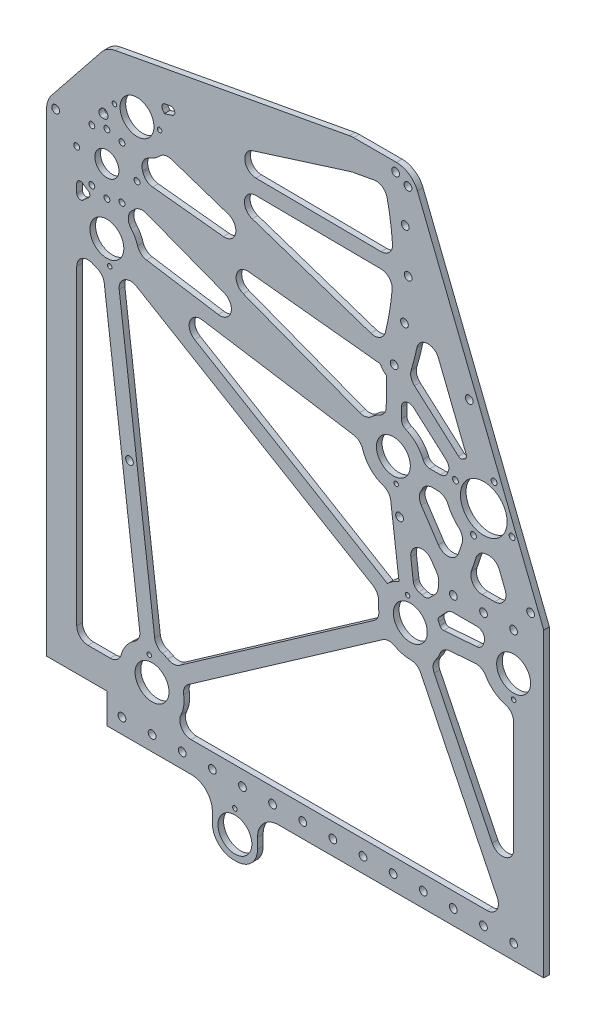
SolidWorks part; units mm, degrees
material "6061 Alloy"
ref_plane "Front Plane" through (0, 0, 0) normal (0, 0, 1) x (1, 0, 0)
ref_plane "Top Plane" through (0, 0, 0) normal (0, 1, 0) x (1, 0, 0)
ref_plane "Right Plane" through (0, 0, 0) normal (1, 0, 0) x (0, 0, -1)
sketch "Sketch1" plane through (0, 0, 0) normal (0, 0, 1) x (1, 0, 0)
  line L0 (0, 0) -> (0, 25.4) construction
  line L1 (0, 25.4) -> (-50.8, 25.4) construction
  line L2 (0, 0) -> (58.42, 0)
  line L3 (-50.8, 25.4) -> (-50.8, 457.2) construction
  line L4 (-50.8, 457.2) -> (12.7, 457.2) construction
  line L6 (76.2, -17.78) -> (76.2, -26.67)
  line L7 (93.98, -44.45) -> (96.52, -44.45)
  line L8 (114.3, -26.67) -> (114.3, -17.78)
  line L9 (132.08, 0) -> (355.6, 0)
  line L11 (355.6, 254) -> (355.6, 0)
  line L12 (249.1012, 521.3987) -> (355.6, 254)
  line L13 (330.2, 241.3) -> (304.8, 241.3) construction
  line L14 (305.0409, 317.5) -> (313.7282, 341.3682) construction
  line L15 (305.0409, 317.5) -> (313.7282, 341.3682) construction
  line L16 (-12.7, 355.6) -> (25.4, 50.8) construction
  line L17 (228.8409, 317.5) -> (243.1284, 203.2) construction
  line L19 (235.9847, 260.35) -> (2.849, 231.208) construction
  line L24 (-12.7, 435.6959) -> (12.7, 410.2959) construction
  line L25 (-12.7, 410.2959) -> (293.3509, 410.2959) construction
  line L27 (-63.5, 25.4) -> (-63.5, 425.1176)
  line L29 (0, 0) -> (-12.7, 0)
  line L30 (-12.7, 0) -> (-12.7, 25.4)
  line L31 (-63.5, 25.4) -> (-12.7, 25.4)
  line L32 (241.1463, 520.7) -> (292.8368, 390.9149) construction
  line L33 (12.7, 457.2) -> (229.4868, 384.6642) construction
  line L34 (12.7, 457.2) -> (229.4868, 384.6642) construction
  line L35 (12.7, 457.2) -> (238.1649, 419.4701) construction
  line L36 (12.7, 457.2) -> (230.7197, 525.9413) construction
  line L37 (195.2663, 533.4) -> (231.4032, 533.4)
  line L39 (191.8054, 533.083) -> (-5.7197, 496.5896)
  line L40 (-17.1343, 489.7571) -> (-59.3256, 437.0181)
  circle A0 centre (12.7, 457.2) radius 14.2875
  circle A1 centre (0, 12.7) radius 3.2639
  circle A3 centre (95.25, -25.4) radius 14.2875
  circle A4 centre (95.25, -6.35) radius 1.8987
  circle A5 centre (330.2, 209.55) radius 14.2875
  circle A6 centre (330.2, 241.3) radius 3.2639
  circle A7 centre (304.8, 241.3) radius 3.2639
  circle A8 centre (279.4, 241.3) radius 3.2639
  circle A9 centre (330.2, 190.5) radius 1.8987
  circle A10 centre (-6.35, 457.2) radius 1.8986
  circle A11 centre (31.75, 457.2) radius 1.8986
  circle A12 centre (-12.7, 410.2959) radius 25.4 construction
  circle A13 centre (-12.7, 435.6959) radius 2.4892
  circle A14 centre (12.7, 410.2959) radius 2.4892
  circle A15 centre (-12.7, 384.8959) radius 2.4892
  circle A17 centre (-12.7, 410.2959) radius 10.16
  circle A18 centre (305.0409, 317.5) radius 19.685
  circle A27 centre (-12.7, 355.6) radius 14.2875
  circle A28 centre (25.4, 50.8) radius 14.2875
  circle A29 centre (228.8409, 317.5) radius 14.2875
  circle A30 centre (243.1284, 203.2) radius 14.2875
  circle A31 centre (305.0409, 317.5) radius 25.4 construction
  circle A33 centre (313.7282, 341.3682) radius 2.4892
  circle A36 centre (328.9091, 308.8127) radius 2.4892
  circle A37 centre (296.3536, 293.6318) radius 2.4892
  circle A38 centre (281.1727, 326.1873) radius 2.4892
  circle A39 centre (241.1463, 520.7) radius 3.2639
  circle A41 centre (6.35, 203.2) radius 3.2639
  circle A43 centre (234.0392, 275.9136) radius 3.2639
  circle A48 centre (25.4, 12.7) radius 3.2639
  circle A50 centre (50.8, 12.7) radius 3.2639
  circle A51 centre (0, 388.2988) radius 2.4892
  circle A52 centre (-25.4, 388.2988) radius 2.4892
  circle A53 centre (-10.3371, 336.6971) radius 1.8986
  circle A54 centre (23.0371, 69.7029) radius 1.8986
  circle A55 centre (231.2038, 298.5971) radius 1.8986
  circle A56 centre (240.7656, 222.1029) radius 1.8987
  circle A57 centre (292.8368, 390.9149) radius 3.2639
  circle A58 centre (344.5273, 261.1297) radius 3.2639
  circle A59 centre (229.4868, 384.6642) radius 3.2639
  circle A60 centre (238.1649, 419.4701) radius 3.2639
  circle A61 centre (241.2913, 455.2051) radius 3.2639
  circle A62 centre (238.789, 490.9892) radius 3.2639
  circle A63 centre (230.7197, 525.9413) radius 3.2639
  arc A64 (114.3, -26.67) -> (96.52, -44.45) centre (96.52, -26.67) cw
  arc A65 (76.2, -26.67) -> (93.98, -44.45) centre (93.98, -26.67) ccw
  arc A66 (58.42, 0) -> (76.2, -17.78) centre (58.42, -17.78) cw
  arc A67 (132.08, 0) -> (114.3, -17.78) centre (132.08, -17.78) ccw
  arc A68 (249.1012, 521.3987) -> (231.4032, 533.4) centre (231.4032, 514.35) ccw
  arc A69 (195.2663, 533.4) -> (191.8054, 533.083) centre (195.2663, 514.35) ccw
  arc A70 (-63.5, 425.1176) -> (-59.3256, 437.0181) centre (-44.45, 425.1176) cw
  arc A71 (-5.7197, 496.5896) -> (-17.1343, 489.7571) centre (-2.2588, 477.8567) ccw
  circle A72 centre (-55.88, 428.625) radius 3.2639
  circle A82 centre (76.2, 12.7) radius 3.2639
  circle A83 centre (101.6, 12.7) radius 3.2639
  circle A84 centre (127, 12.7) radius 3.2639
  circle A85 centre (152.4, 12.7) radius 3.2639
  circle A86 centre (177.8, 12.7) radius 3.2639
  circle A87 centre (203.2, 12.7) radius 3.2639
  circle A88 centre (228.6, 12.7) radius 3.2639
  circle A89 centre (254, 12.7) radius 3.2639
  circle A90 centre (279.4, 12.7) radius 3.2639
  circle A91 centre (304.8, 12.7) radius 3.2639
  circle A92 centre (330.2, 12.7) radius 3.2639
  circle A93 centre (-38.1, 410.2959) radius 2.4892
  circle A94 centre (-25.4, 432.2929) radius 2.4892
  circle A95 centre (0, 432.2929) radius 2.4892
  circle A96 centre (-38.1, 410.2959) radius 2.4892 [skipped]
  point P51 (-12.7, 410.2959)
  point P126 (114.3, -44.45)
  point P129 (76.2, -44.45)
  point P132 (76.2, 0)
  point P135 (114.3, 0)
  point P139 (244.3213, 533.4)
  point P142 (193.5213, 533.4)
  point P145 (-63.5, 431.8)
  point P148 (-12.7, 495.3)
  point P173 (-12.7, 410.2959)
  dimension "D8" = 19.05
  dimension "D11" = 6.5278
  dimension "D14" = 19.05
  dimension "D15" = 6
  dimension "D22" = 3.7973
  dimension "D25" = 12.7
  dimension "D29" = 3
  dimension "D31" = 12.7
  dimension "D35" = 63.5
  dimension "D36" = 50.8
  dimension "D37" = 4.9784
  dimension "D41" = 20.32
  dimension "D44" = 28.575
  dimension "D43" = 39.37
  dimension "D52" = 50.8
  dimension "D53" = 139.7
  dimension "D69" = 14
  dimension "D13" = 19.05
  dimension "D55" = 533.4
  dimension "D66" = 17.78
  dimension "D75" = 19.05
  dimension "D76" = 7.62
  dimension "D1" = 50.8
  dimension "D2" = 355.6
  dimension "D3" = 25.4
  dimension "D4" = 63.5
  dimension "D5" = 431.8
  dimension "D6" = 431.8
  dimension "D7" = 304.8
  dimension "D9" = 12.7
  dimension "D10" = 53.34
  dimension "D12" = 19.05
  dimension "D16" = 25.4
  dimension "D17" = 19.05
  dimension "D18" = 44.45
  dimension "D19" = 127
  dimension "D20" = 38.1
  dimension "D21" = 19.05
  dimension "D23" = 209.55
  dimension "D24" = 25.4
  dimension "D26" = 254
  dimension "D27" = 76.2
  dimension "D28" = 31.75
  dimension "D30" = 25.4
  dimension "D32" = 19.05
  dimension "D33" = 19.05
  dimension "D34" = 19.05
  dimension "D38" = 25.4
  dimension "D39" = 3
  dimension "D42" = 203.2
  dimension "D45" = 50.8
  dimension "D46" = 76.2
  dimension "D47" = 355.6
  dimension "D48" = 38.1
  dimension "D49" = 139.7
  dimension "D50" = 25.4
  dimension "D51" = 234.95
  dimension "D54" = 228.6
  dimension "D57" = 70
  dimension "D58" = 25.4
  dimension "D59" = 12.7
  dimension "D60" = 3.175
  dimension "D63" = 5
  dimension "D64" = 9
  dimension "D68" = 17.5
  dimension "D70" = 406.4
  dimension "D71" = 50.8
  dimension "D72" = 63.5
  dimension "D73" = 50.8
  dimension "D74" = 41.91
  dimension "D77" = 3.175
  dimension "D40" = 4
  dimension "D56" = 4
extrude "Boss-Extrude1" add sketch "Sketch1" along normal blind 4.7625
sketch "Sketch2" plane through (0, 0, 4.7625) normal (0, 0, 1) x (1, 0, 0)
  line L0 (25.4, 50.8) -> (-12.7, 355.6) construction
  line L1 (25.4, 50.8) -> (243.1284, 203.2) construction
  line L2 (243.1284, 203.2) -> (-12.7, 355.6) construction
  line L3 (228.8409, 317.5) -> (-12.7, 355.6) construction
  line L4 (-12.7, 355.6) -> (-12.7, 410.2959) construction
  line L5 (-12.7, 410.2959) -> (228.8409, 317.5) construction
  line L6 (12.7, 457.2) -> (229.4868, 384.6642) construction
  line L7 (-12.7, 410.2959) -> (229.4868, 384.6642) construction
  line L8 (-12.7, 410.2959) -> (12.7, 457.2) construction
  line L9 (12.7, 457.2) -> (230.7197, 525.9413) construction
  line L10 (243.1284, 203.2) -> (228.8409, 317.5) construction
  line L11 (243.1284, 203.2) -> (330.2, 25.4) construction
  line L12 (132.08, 0) -> (355.6, 0) construction
  line L13 (355.6, 0) -> (355.6, 254) construction
  line L14 (243.1284, 203.2) -> (330.2, 209.55) construction
  line L15 (243.1284, 203.2) -> (279.4, 241.3) construction
  line L16 (305.0409, 317.5) -> (228.8409, 317.5) construction
  line L17 (228.8409, 317.5) -> (229.4868, 384.6642) construction
  line L18 (12.7, 457.2) -> (241.2913, 455.2051) construction
  line L19 (305.0409, 317.5) -> (229.4868, 384.6642) construction
  line L20 (-38.1, 60.325) -> (-38.1, 322.7192)
  line L21 (-18.7992, 447.0162) -> (-17.8647, 448.1842)
  line L22 (36.1906, 478.5028) -> (40.8249, 479.359)
  line L23 (266.8242, 408.2528) -> (290.2311, 349.4825)
  line L25 (307.8591, 25.4) -> (58.2808, 25.4)
  line L28 (-63.5, 425.1176) -> (-63.5, 25.4) construction
  line L29 (-17.1343, 489.7571) -> (-59.3256, 437.0181) construction
  line L30 (191.8054, 533.083) -> (-5.7197, 496.5896) construction
  line L31 (355.6, 254) -> (249.1012, 521.3987) construction
  line L34 (279.4, 241.3) -> (330.2, 241.3) construction
  line L35 (303.6283, 254) -> (314.2133, 254)
  line L36 (279.4, 228.6) -> (299.3763, 228.6)
  line L37 (279.4, 241.3) -> (228.8409, 317.5) construction
  line L38 (279.4, 241.3) -> (305.0409, 317.5) construction
  line L39 (223.8439, 222.0794) -> (61.3103, 318.9026)
  line L40 (12.2985, 333.3167) -> (211.6302, 214.5725)
  line L41 (219.8322, 179.1427) -> (55.9789, 64.4528)
  line L42 (48.6962, 74.8573) -> (212.5495, 189.5472)
  line L43 (316.4134, 39.1142) -> (251.8869, 170.8773)
  line L44 (263.2926, 176.4628) -> (312.1207, 76.756)
  line L45 (-14.9226, 322.1855) -> (15.0207, 82.6393)
  line L46 (27.6226, 84.2145) -> (-2.3207, 323.7607)
  line L47 (195.3723, 316.3507) -> (67.6691, 336.4943)
  line L48 (20.7686, 356.7493) -> (81.2842, 347.2037)
  line L49 (102.3324, 372.9049) -> (200.4246, 335.2196)
  line L50 (20.5883, 390.7046) -> (86.1842, 365.5038)
  line L51 (276.384, 199.2584) -> (297.8682, 200.8252)
  line L52 (271.2098, 211.6148) -> (298.9961, 213.6412)
  line L53 (259.7827, 229.9031) -> (264.076, 234.4129)
  line L54 (274.2087, 226.6376) -> (267.4608, 219.5496)
  line L55 (298.6892, 278.7133) -> (294.6007, 266.5627)
  line L56 (283.7249, 274.0635) -> (286.6524, 282.7636)
  line L57 (233.5741, 228.4396) -> (226.6183, 284.0855)
  line L58 (243.524, 251.2307) -> (245.6062, 234.5733)
  line L59 (266.7604, 271.8351) -> (252.3111, 293.6124)
  line L60 (260.9123, 257.6783) -> (265.5092, 250.7501)
  line L61 (259.6646, 323.85) -> (268.4471, 323.85)
  line L62 (261.7217, 311.15) -> (266.2539, 311.15)
  line L63 (283.654, 345.0083) -> (246.6005, 377.9472)
  line L64 (246.1366, 361.367) -> (273.4723, 337.0667)
  line L65 (217.881, 379.507) -> (106.7508, 391.2684)
  line L66 (25.8567, 412.6007) -> (85.5239, 406.2859)
  line L67 (218.4003, 449.0546) -> (112.8716, 449.9756)
  line L68 (112.9824, 462.6751) -> (218.5111, 461.7542)
  line L69 (41.8668, 440.7449) -> (89.5487, 424.7907)
  line L70 (209.8453, 397.9321) -> (109.7661, 431.4182)
  line L71 (223.0313, 373.7272) -> (222.8074, 350.4403)
  line L72 (235.487, 348.2612) -> (235.568, 356.6821)
  line L73 (35.8063, 471.1436) -> (42.3565, 473.2088)
  line L74 (110.2013, 481.2839) -> (193.0823, 507.4162)
  line L75 (-63.5, 25.4) -> (-12.7, 25.4)
  line L76 (-12.7, 25.4) -> (-12.7, 0)
  line L77 (-12.7, 0) -> (355.6, 0)
  line L78 (355.6, 0) -> (355.6, 254)
  line L79 (355.6, 254) -> (244.3213, 533.4)
  line L80 (244.3213, 533.4) -> (193.5213, 533.4)
  line L81 (231.4032, 533.4) -> (195.2663, 533.4) construction
  line L82 (193.5213, 533.4) -> (-12.7, 495.3)
  line L83 (-12.7, 495.3) -> (-63.5, 431.8)
  line L84 (-63.5, 431.8) -> (-63.5, 25.4)
  line L85 (-38.1, 375.9918) -> (-38.1, 383.3551)
  line L86 (194.216, 507.6985) -> (212.488, 511.0743)
  line L87 (323.1294, 25.4) -> (330.2, 25.4) construction
  line L88 (318.1698, 279.3335) -> (323.0623, 267.0494)
  line L89 (330.2, 174.3018) -> (330.2, 80.9452)
  line L90 (330.2, 25.4) -> (330.2, 39.8381) construction
  line L92 (-9.8482, 50.8) -> (-28.575, 50.8)
  circle A1 centre (-10.3371, 336.6971) radius 1.8986
  circle A2 centre (-10.3371, 336.6971) radius 1.8986 construction
  circle A3 centre (230.7197, 525.9413) radius 3.2639
  circle A4 centre (230.7197, 525.9413) radius 3.2639 construction
  circle A5 centre (12.7, 457.2) radius 14.2875
  circle A6 centre (12.7, 457.2) radius 14.2875 construction
  circle A7 centre (0, 12.7) radius 3.2639
  circle A8 centre (0, 12.7) radius 3.2639 construction
  circle A9 centre (95.25, -25.4) radius 14.2875
  circle A10 centre (95.25, -25.4) radius 14.2875 construction
  circle A11 centre (330.2, 209.55) radius 14.2875
  circle A12 centre (330.2, 209.55) radius 14.2875 construction
  circle A13 centre (95.25, -6.35) radius 1.8987
  circle A14 centre (95.25, -6.35) radius 1.8987 construction
  circle A15 centre (330.2, 190.5) radius 1.8987
  circle A16 centre (330.2, 190.5) radius 1.8987 construction
  circle A17 centre (330.2, 241.3) radius 3.2639
  circle A18 centre (330.2, 241.3) radius 3.2639 construction
  circle A19 centre (304.8, 241.3) radius 3.2639
  circle A20 centre (304.8, 241.3) radius 3.2639 construction
  circle A21 centre (279.4, 241.3) radius 3.2639
  circle A22 centre (279.4, 241.3) radius 3.2639 construction
  circle A23 centre (-6.35, 457.2) radius 1.8986
  circle A24 centre (-6.35, 457.2) radius 1.8986 construction
  circle A25 centre (31.75, 457.2) radius 1.8986
  circle A26 centre (31.75, 457.2) radius 1.8986 construction
  circle A27 centre (-12.7, 435.6959) radius 2.4892
  circle A28 centre (-12.7, 435.6959) radius 2.4892 construction
  circle A29 centre (305.0409, 317.5) radius 19.685
  arc A30 (296.0039, 334.988) -> (310.5014, 298.5875) centre (305.0409, 317.5) ccw construction
  circle A31 centre (-12.7, 410.2959) radius 10.16
  circle A32 centre (-12.7, 410.2959) radius 10.16 construction
  circle A33 centre (12.7, 410.2959) radius 2.4892
  circle A34 centre (12.7, 410.2959) radius 2.4892 construction
  circle A35 centre (-12.7, 384.8959) radius 2.4892
  circle A36 centre (-12.7, 384.8959) radius 2.4892 construction
  circle A39 centre (313.7282, 341.3682) radius 2.4892
  circle A40 centre (313.7282, 341.3682) radius 2.4892 construction
  circle A41 centre (241.1463, 520.7) radius 3.2639
  circle A42 centre (241.1463, 520.7) radius 3.2639 construction
  circle A43 centre (-12.7, 355.6) radius 14.2875
  circle A44 centre (-12.7, 355.6) radius 14.2875 construction
  circle A45 centre (328.9091, 308.8127) radius 2.4892
  circle A46 centre (328.9091, 308.8127) radius 2.4892 construction
  circle A47 centre (25.4, 50.8) radius 14.2875
  arc A48 (37.105, 58.993) -> (23.6279, 64.9772) centre (25.4, 50.8) ccw construction
  circle A49 centre (228.8409, 317.5) radius 14.2875
  circle A50 centre (228.8409, 317.5) radius 14.2875 construction
  circle A51 centre (243.1284, 203.2) radius 14.2875
  circle A52 centre (243.1284, 203.2) radius 14.2875 construction
  circle A53 centre (296.3536, 293.6318) radius 2.4892
  circle A54 centre (296.3536, 293.6318) radius 2.4892 construction
  circle A55 centre (281.1727, 326.1873) radius 2.4892
  circle A56 centre (281.1727, 326.1873) radius 2.4892 construction
  circle A57 centre (6.35, 203.2) radius 3.2639
  circle A58 centre (6.35, 203.2) radius 3.2639 construction
  circle A59 centre (229.4868, 384.6642) radius 3.2639
  circle A60 centre (229.4868, 384.6642) radius 3.2639 construction
  circle A61 centre (234.0392, 275.9136) radius 3.2639
  circle A62 centre (234.0392, 275.9136) radius 3.2639 construction
  circle A63 centre (76.2, 12.7) radius 3.2639
  circle A64 centre (76.2, 12.7) radius 3.2639 construction
  circle A65 centre (101.6, 12.7) radius 3.2639
  circle A66 centre (101.6, 12.7) radius 3.2639 construction
  circle A67 centre (127, 12.7) radius 3.2639
  circle A68 centre (127, 12.7) radius 3.2639 construction
  circle A69 centre (25.4, 12.7) radius 3.2639
  circle A70 centre (25.4, 12.7) radius 3.2639 construction
  circle A71 centre (23.0371, 69.7029) radius 1.8986
  circle A72 centre (23.0371, 69.7029) radius 1.8986 construction
  circle A73 centre (50.8, 12.7) radius 3.2639
  circle A74 centre (50.8, 12.7) radius 3.2639 construction
  circle A75 centre (238.1649, 419.4701) radius 3.2639
  circle A76 centre (238.1649, 419.4701) radius 3.2639 construction
  circle A77 centre (231.2038, 298.5971) radius 1.8987
  circle A78 centre (231.2038, 298.5971) radius 1.8986 construction
  circle A79 centre (240.7656, 222.1029) radius 1.8987
  circle A80 centre (240.7656, 222.1029) radius 1.8987 construction
  circle A81 centre (292.8368, 390.9149) radius 3.2639
  circle A82 centre (292.8368, 390.9149) radius 3.2639 construction
  circle A83 centre (344.5273, 261.1297) radius 3.2639
  circle A84 centre (344.5273, 261.1297) radius 3.2639 construction
  circle A85 centre (241.2913, 455.2051) radius 3.2639
  circle A86 centre (241.2913, 455.2051) radius 3.2639 construction
  circle A87 centre (238.789, 490.9892) radius 3.2639
  circle A88 centre (238.789, 490.9892) radius 3.2639 construction
  circle A89 centre (-55.88, 428.625) radius 3.2639
  circle A90 centre (-55.88, 428.625) radius 3.2639 construction
  circle A91 centre (152.4, 12.7) radius 3.2639
  circle A92 centre (152.4, 12.7) radius 3.2639 construction
  circle A93 centre (177.8, 12.7) radius 3.2639
  circle A94 centre (177.8, 12.7) radius 3.2639 construction
  circle A95 centre (203.2, 12.7) radius 3.2639
  circle A96 centre (203.2, 12.7) radius 3.2639 construction
  circle A97 centre (228.6, 12.7) radius 3.2639
  circle A98 centre (228.6, 12.7) radius 3.2639 construction
  circle A99 centre (254, 12.7) radius 3.2639
  circle A100 centre (254, 12.7) radius 3.2639 construction
  circle A101 centre (279.4, 12.7) radius 3.2639
  circle A102 centre (279.4, 12.7) radius 3.2639 construction
  circle A103 centre (304.8, 12.7) radius 3.2639
  circle A104 centre (304.8, 12.7) radius 3.2639 construction
  circle A105 centre (330.2, 12.7) radius 3.2639
  circle A106 centre (330.2, 12.7) radius 3.2639 construction
  arc A107 (266.9271, 243.6908) -> (266.7013, 241.1174) centre (279.4, 241.3) ccw
  arc A109 (252.8873, 228.3613) -> (250.235, 229.235) centre (243.1284, 203.2) ccw
  arc A110 (203.0063, 309.6963) -> (220.2123, 291.9291) centre (228.8409, 317.5) ccw
  arc A111 (22.8616, 432.1987) -> (32.0241, 438.3611) centre (12.7, 457.2) ccw
  arc A112 (8.4925, 386.654) -> (10.2788, 388.3861) centre (-12.7, 410.2959) ccw
  arc A113 (1.9575, 332.9399) -> (2.1741, 333.0814) centre (-12.7, 355.6) ccw
  arc A114 (38.5818, 74.3492) -> (34.0286, 76.3709) centre (25.4, 50.8) ccw
  arc A115 (305.2475, 219.831) -> (304.5658, 217.9888) centre (330.2, 209.55) ccw
  arc A116 (275.1203, 329.8912) -> (274.4461, 328.118) centre (305.0409, 317.5) ccw
  circle A117 centre (12.7, 457.2) radius 228.6 construction
  arc A118 (223.5193, 503.762) -> (228.097, 471.9286) centre (12.7, 457.2) cw
  arc A119 (248.6609, 406.7211) -> (243.8062, 387.8053) centre (12.7, 457.2) cw
  arc A121 (10.7425, 73.4601) -> (-0.653, 57.8402) centre (25.4, 50.8) ccw
  arc A122 (-24.4337, 331.2968) -> (-21.3286, 330.0291) centre (-12.7, 355.6) ccw
  arc A123 (13.1346, 363.4037) -> (7.6632, 373.3106) centre (-12.7, 355.6) ccw
  arc A124 (-32.9045, 385.8043) -> (-28.6759, 382.8581) centre (-12.7, 410.2959) ccw
  arc A125 (-28.4236, 377.5338) -> (-32.5855, 373.8453) centre (-12.7, 355.6) ccw
  arc A126 (-14.7456, 441.9799) -> (-15.9908, 441.8749) centre (-12.7, 410.2959) ccw
  arc A127 (-12.4291, 447.3586) -> (-12.0397, 446.4169) centre (12.7, 457.2) ccw
  arc A128 (35.8063, 471.1436) -> (34.234, 473.4669) centre (12.7, 457.2) ccw
  arc A129 (227.8072, 438.7145) -> (222.1061, 404.6464) centre (12.7, 457.2) cw
  arc A130 (217.881, 379.507) -> (223.0313, 373.7272) centre (229.4868, 384.6642) ccw
  arc A131 (17.7301, 419.3551) -> (17.4139, 420.3565) centre (-12.7, 410.2959) ccw
  arc A132 (217.3415, 341.9149) -> (210.3624, 337.169) centre (228.8409, 317.5) ccw
  arc A133 (253.7934, 327.781) -> (239.3613, 342.3525) centre (228.8409, 317.5) ccw
  arc A134 (252.0548, 303.7363) -> (253.1441, 305.7663) centre (228.8409, 317.5) ccw
  arc A135 (275.0691, 305.233) -> (283.8558, 293.0056) centre (305.0409, 317.5) ccw
  arc A136 (288.8671, 345.557) -> (287.4846, 344.7133) centre (305.0409, 317.5) ccw
  arc A137 (306.8146, 196.0797) -> (323.1598, 183.497) centre (330.2, 209.55) ccw
  arc A138 (279.0052, 228.6061) -> (279.4, 228.6) centre (279.4, 241.3) ccw
  arc A139 (268.0473, 213.5623) -> (266.957, 215.8698) centre (243.1284, 203.2) ccw
  arc A140 (233.5741, 228.4396) -> (223.8439, 222.0794) centre (243.1284, 203.2) ccw
  arc A141 (216.2441, 205.5574) -> (216.4895, 198.8765) centre (243.1284, 203.2) ccw
  arc A142 (229.9466, 179.6508) -> (243.2793, 176.2129) centre (243.1284, 203.2) ccw
  arc A143 (264.3551, 186.5341) -> (268.2207, 193.2651) centre (243.1284, 203.2) ccw
  arc A144 (49.7032, 39.0663) -> (52.0389, 55.1235) centre (25.4, 50.8) ccw
  arc A145 (307.1087, 285.1811) -> (308.3481, 285.2843) centre (305.0409, 317.5) ccw
  arc A146 (218.5111, 461.7542) -> (228.097, 471.9286) centre (218.5942, 471.2788) ccw
  arc A147 (223.5193, 503.762) -> (212.488, 511.0743) centre (214.2185, 501.7078) ccw
  arc A148 (193.0823, 507.4162) -> (194.216, 507.6985) centre (195.9465, 498.332) cw
  arc A149 (112.9824, 462.6751) -> (110.2013, 481.2839) centre (113.0655, 472.1997) cw
  arc A150 (109.7661, 431.4182) -> (112.8716, 449.9756) centre (112.7885, 440.4509) cw
  arc A151 (227.8072, 438.7145) -> (218.4003, 449.0546) centre (218.3171, 439.53) ccw
  arc A152 (222.1061, 404.6464) -> (209.8453, 397.9321) centre (212.8676, 406.9649) cw
  arc A153 (248.6609, 406.7211) -> (266.8242, 408.2528) centre (257.9752, 404.7285) cw
  arc A154 (246.6005, 377.9472) -> (243.8062, 387.8053) centre (252.9288, 385.066) cw
  arc A155 (25.8567, 412.6007) -> (17.7301, 419.3551) centre (26.8592, 422.0728) cw
  arc A156 (17.4139, 420.3565) -> (22.8616, 432.1987) centre (26.4481, 423.3747) cw
  arc A157 (41.8668, 440.7449) -> (32.0241, 438.3611) centre (38.8444, 431.7121) ccw
  arc A158 (89.5487, 424.7907) -> (85.5239, 406.2859) centre (86.5264, 415.758) cw
  arc A159 (-2.3207, 323.7607) -> (1.9575, 332.9399) centre (7.1308, 324.9422) cw
  arc A160 (12.2985, 333.3167) -> (2.1741, 333.0814) centre (7.4238, 325.1337) ccw
  arc A161 (-24.4337, 331.2968) -> (-38.1, 322.7192) centre (-28.575, 322.7192) ccw
  arc A162 (-14.9226, 322.1855) -> (-21.3286, 330.0291) centre (-24.374, 321.0041) ccw
  arc A163 (8.4925, 386.654) -> (7.6632, 373.3106) centre (14.8502, 379.5614) ccw
  arc A164 (20.5883, 390.7046) -> (10.2788, 388.3861) centre (17.1724, 381.8132) ccw
  arc A165 (264.076, 234.4129) -> (266.7013, 241.1174) centre (257.1773, 240.9805) ccw
  arc A166 (265.5092, 250.7501) -> (266.9271, 243.6908) centre (257.5724, 245.4839) cw
  arc A167 (260.9123, 257.6783) -> (243.524, 251.2307) centre (252.9755, 252.4122) ccw
  arc A168 (252.3111, 293.6124) -> (252.0548, 303.7363) centre (260.248, 298.8785) cw
  arc A169 (261.7217, 311.15) -> (253.1441, 305.7663) centre (261.7217, 301.625) ccw
  arc A170 (266.2539, 311.15) -> (275.0691, 305.233) centre (266.2539, 301.625) cw
  arc A171 (286.6524, 282.7636) -> (283.8558, 293.0056) centre (277.6248, 285.8013) ccw
  arc A172 (283.7249, 274.0635) -> (266.7604, 271.8351) centre (274.6973, 277.1012) cw
  arc A173 (308.3481, 285.2843) -> (318.1698, 279.3335) centre (309.3209, 275.8091) cw
  arc A174 (298.6892, 278.7133) -> (307.1087, 285.1811) centre (307.7169, 275.6755) cw
  arc A175 (294.6007, 266.5627) -> (303.6283, 254) centre (303.6283, 263.525) ccw
  arc A176 (314.2133, 254) -> (323.0623, 267.0494) centre (314.2133, 263.525) ccw
  arc A177 (200.4246, 335.2196) -> (210.3624, 337.169) centre (203.8405, 344.111) ccw
  arc A178 (222.8074, 350.4403) -> (217.3415, 341.9149) centre (213.2828, 350.5319) cw
  arc A179 (20.7686, 356.7493) -> (13.1346, 363.4037) centre (22.2527, 366.1579) cw
  arc A180 (86.1842, 365.5038) -> (81.2842, 347.2037) centre (82.7682, 356.6124) cw
  arc A181 (67.6691, 336.4943) -> (61.3103, 318.9026) centre (66.185, 327.0856) ccw
  arc A182 (195.3723, 316.3507) -> (203.0063, 309.6963) centre (193.8882, 306.9421) cw
  arc A183 (226.6183, 284.0855) -> (220.2123, 291.9291) centre (217.1669, 282.9041) ccw
  arc A184 (-38.1, 60.325) -> (-28.575, 50.8) centre (-28.575, 60.325) ccw
  arc A185 (-0.653, 57.8402) -> (-9.8482, 50.8) centre (-9.8482, 60.325) cw
  arc A186 (15.0207, 82.6393) -> (10.7425, 73.4601) centre (5.5692, 81.4578) cw
  arc A187 (211.6302, 214.5725) -> (216.2441, 205.5574) centre (206.7555, 206.3894) cw
  arc A188 (212.5495, 189.5472) -> (216.4895, 198.8765) centre (207.0875, 197.3505) ccw
  arc A189 (27.6226, 84.2145) -> (34.0286, 76.3709) centre (37.074, 85.3959) ccw
  arc A190 (48.6962, 74.8573) -> (38.5818, 74.3492) centre (43.2343, 82.6607) cw
  arc A191 (263.2926, 176.4628) -> (264.3551, 186.5341) centre (271.8469, 180.652) cw
  arc A192 (276.384, 199.2584) -> (268.2207, 193.2651) centre (277.0768, 189.7586) ccw
  arc A193 (297.8682, 200.8252) -> (306.8146, 196.0797) centre (298.561, 191.3255) cw
  arc A194 (323.1598, 183.497) -> (330.2, 174.3018) centre (320.675, 174.3018) cw
  arc A195 (312.1207, 76.756) -> (330.2, 80.9452) centre (320.675, 80.9452) ccw
  arc A196 (55.9789, 64.4528) -> (52.0389, 55.1235) centre (61.4409, 56.6495) ccw
  arc A197 (49.7032, 39.0663) -> (58.2808, 25.4) centre (58.2808, 34.925) ccw
  arc A198 (219.8322, 179.1427) -> (229.9466, 179.6508) centre (225.2942, 171.3393) cw
  arc A199 (251.8869, 170.8773) -> (243.2793, 176.2129) centre (243.3325, 166.6881) ccw
  arc A200 (316.4134, 39.1142) -> (307.8591, 25.4) centre (307.8591, 34.925) cw
  arc A201 (245.6062, 234.5733) -> (250.235, 229.235) centre (251.9072, 235.3609) ccw
  arc A202 (259.7827, 229.9031) -> (252.8873, 228.3613) centre (255.1835, 234.2816) cw
  arc A203 (274.2087, 226.6376) -> (279.0052, 228.6061) centre (278.8078, 222.2592) cw
  arc A204 (298.9961, 213.6412) -> (304.5658, 217.9888) centre (298.5342, 219.9744) ccw
  arc A205 (299.3763, 228.6) -> (305.2475, 219.831) centre (299.3763, 222.25) cw
  arc A206 (235.568, 356.6821) -> (246.1366, 361.367) centre (241.9177, 356.6211) cw
  arc A207 (235.487, 348.2612) -> (239.3613, 342.3525) centre (241.8367, 348.2001) ccw
  arc A208 (259.6646, 323.85) -> (253.7934, 327.781) centre (259.6646, 330.2) cw
  arc A209 (273.4723, 337.0667) -> (275.1203, 329.8912) centre (269.2535, 332.3208) cw
  arc A210 (268.4471, 323.85) -> (274.4461, 328.118) centre (268.4471, 330.2) ccw
  arc A211 (34.234, 473.4669) -> (36.1906, 478.5028) centre (36.7674, 475.3807) cw
  arc A212 (42.3565, 473.2088) -> (40.8249, 479.359) centre (41.4017, 476.2369) ccw
  arc A213 (-32.5855, 373.8453) -> (-38.1, 375.9918) centre (-34.925, 375.9918) cw
  arc A214 (-28.6759, 382.8581) -> (-28.4236, 377.5338) centre (-30.2735, 380.1143) cw
  arc A215 (-32.9045, 385.8043) -> (-38.1, 383.3551) centre (-34.925, 383.3551) ccw
  arc A216 (-15.9908, 441.8749) -> (-18.7992, 447.0162) centre (-16.3199, 445.0328) cw
  arc A217 (-17.8647, 448.1842) -> (-12.4291, 447.3586) centre (-15.3855, 446.2008) cw
  arc A218 (-12.0397, 446.4169) -> (-14.7456, 441.9799) centre (-14.9502, 445.1483) cw
  arc A219 (267.4608, 219.5496) -> (266.957, 215.8698) centre (269.7604, 217.3604) ccw
  arc A220 (271.2098, 211.6148) -> (268.0473, 213.5623) centre (270.9789, 214.7814) cw
  arc A221 (288.8671, 345.557) -> (290.2311, 349.4825) centre (287.2814, 348.3077) ccw
  arc A222 (283.654, 345.0083) -> (287.4846, 344.7133) centre (285.7634, 347.3813) ccw
  arc A223 (102.3324, 372.9049) -> (106.7508, 391.2684) centre (105.7484, 381.7963) cw
  point P181 (304.8, 241.3)
  point P185 (221.3419, 512.7101)
  point P190 (193.6405, 507.5922)
  point P299 (18.9041, 413.3366)
  point P326 (248.634, 299.1544)
  point P331 (273.2846, 311.15)
  point P334 (288.8947, 289.4271)
  point P339 (315.2143, 286.7544)
  point P342 (300.9315, 285.3768)
  point P351 (222.7434, 343.7897)
  point P354 (14.1989, 357.7856)
  point P369 (15.8456, 76.0396)
  point P372 (217.3442, 211.1686)
  point P375 (217.9984, 193.3611)
  point P382 (260.3674, 182.436)
  point P387 (304.5015, 201.309)
  point P399 (225.281, 182.9566)
  point P402 (248.9617, 176.8505)
  point P412 (276.4155, 228.9557)
  point P423 (255.0707, 323.85)
  point P434 (-38.1, 364.7195)
  point P443 (-13.9674, 453.0559)
  point P450 (268.8269, 211.441)
  dimension "D64" = 12.7
  dimension "D65" = 12.7
  dimension "D66" = 63.5
  dimension "D67" = 12.7
  dimension "D68" = 12.7
  dimension "D69" = 12.7
  dimension "D70" = 12.7
  dimension "D71" = 12.7
  dimension "D72" = 12.7
  dimension "D85" = 12.7
  dimension "D86" = 12.7
  dimension "D87" = 6.35
  dimension "D99" = 6.35
  dimension "D107" = 6.35
  dimension "D111" = 12.7
  dimension "D112" = 12.7
  dimension "D58" = 9.525
  dimension "D59" = 6.35
  dimension "D114" = 3.175
  dimension "D115" = 9.525
  dimension "D54" = 25.4
  dimension "D55" = 25.4
  dimension "D56" = 25.4
  dimension "D57" = 25.4
  dimension "D60" = 25.4
  dimension "D61" = 25.4
  dimension "D62" = 25.4
  dimension "D63" = 25.4
  dimension "D73" = 6.35
  dimension "D74" = 12.7
  dimension "D75" = 6.35
  dimension "D76" = 12.7
  dimension "D77" = 6.35
  dimension "D78" = 12.7
  dimension "D79" = 6.35
  dimension "D80" = 12.7
  dimension "D81" = 6.35
  dimension "D82" = 12.7
  dimension "D83" = 6.35
  dimension "D84" = 12.7
  dimension "D88" = 12.7
  dimension "D89" = 6.35
  dimension "D90" = 12.7
  dimension "D91" = 6.35
  dimension "D92" = 12.7
  dimension "D93" = 6.35
  dimension "D94" = 12.7
  dimension "D95" = 6.35
  dimension "D96" = 12.7
  dimension "D97" = 6.35
  dimension "D98" = 12.7
  dimension "D100" = 12.7
  dimension "D101" = 6.35
  dimension "D102" = 12.7
  dimension "D103" = 6.35
  dimension "D104" = 12.7
  dimension "D105" = 6.35
  dimension "D106" = 12.7
  dimension "D108" = 12.7
  dimension "D109" = 6.35
  dimension "D110" = 12.7
  dimension "D113" = 12.7
  dimension "D1" = 0
  dimension "D2" = 0
  dimension "D3" = 0
  dimension "D4" = 0
  dimension "D5" = 0
  dimension "D6" = 0
  dimension "D7" = 0
  dimension "D8" = 0
  dimension "D9" = 0
  dimension "D10" = 0
  dimension "D11" = 0
  dimension "D12" = 0
  dimension "D13" = 0
  dimension "D14" = 0
  dimension "D15" = 0
  dimension "D16" = 0
  dimension "D17" = 0
  dimension "D18" = 0
  dimension "D20" = 0
  dimension "D21" = 0
  dimension "D22" = 0
  dimension "D23" = 0
  dimension "D24" = 0
  dimension "D25" = 0
  dimension "D26" = 0
  dimension "D27" = 0
  dimension "D28" = 0
  dimension "D29" = 0
  dimension "D30" = 0
  dimension "D31" = 0
  dimension "D32" = 0
  dimension "D33" = 0
  dimension "D34" = 0
  dimension "D35" = 0
  dimension "D36" = 0
  dimension "D37" = 0
  dimension "D38" = 0
  dimension "D39" = 0
  dimension "D40" = 0
  dimension "D41" = 0
  dimension "D42" = 0
  dimension "D43" = 0
  dimension "D44" = 0
  dimension "D45" = 0
  dimension "D46" = 0
  dimension "D47" = 0
  dimension "D48" = 0
  dimension "D49" = 0
  dimension "D50" = 0
  dimension "D51" = 0
  dimension "D52" = 0
  dimension "D53" = 0
extrude "Cut-Extrude1" cut sketch "Sketch2" against normal through all contours A144 L25 L43 A142 L41 | A143 L44 L89 A137 L51 | A145 L55 L35 L88 | A109 L53 A107 L60 L58 | A135 L62 A134 L59 L56 | A133 L61 A116 L64 L72 | A136 L23 A119 L63 | A141 L40 A113 L46 A114 L42 | A122 L20 L92 A121 L45 | A140 L57 A110 L47 L39 | A132 L71 A130 L65 L49 | A129 L67 L70 | A118 L86 L74 L68 | A123 L48 L50 A112 | A131 L66 L69 A111 | A127 L21 A126 | A125 A124 L85 | L36 A205 A115 A204 L52 A220 A139 A219 L54 A203 A138 | L22 A212 L73 A128 A211
